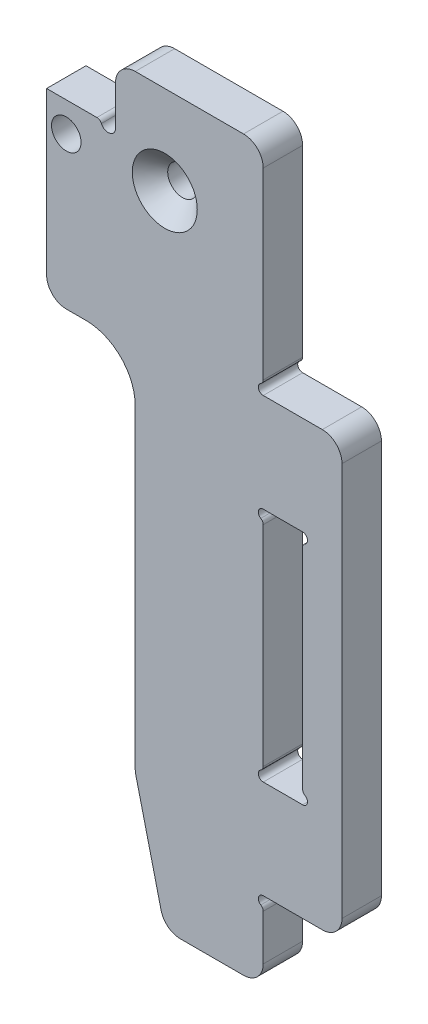
SolidWorks part; units mm, degrees
material "Thornel Mat VMA"
ref_plane "前视基准面" through (0, 0, 0) normal (0, 0, 1) x (1, 0, 0)
ref_plane "上视基准面" through (0, 0, 0) normal (0, 1, 0) x (1, 0, 0)
ref_plane "右视基准面" through (0, 0, 0) normal (1, 0, 0) x (0, 0, -1)
other "Configuration Table"
sketch "草图1" plane through (0, 0, 0) normal (0, 0, 1) x (1, 0, 0)
  line L0 (0, 0) -> (10, 0) construction
  line L1 (-5, -3) -> (10, -65)
  line L2 (-5, -3) -> (20, -3)
  line L3 (-5, -3) -> (-5, 3)
  line L4 (-5, 3) -> (20, 3)
  line L5 (20, -3) -> (20, 3)
  line L6 (-5, -3) -> (20, 3) construction
  line L7 (-5, 3) -> (20, -3) construction
  line L8 (5, 3) -> (20, 3)
  line L9 (5, 3) -> (5, 9)
  line L10 (5, 9) -> (20, 9)
  line L11 (20, 3) -> (20, 9)
  line L12 (10, -65) -> (20, -65)
  line L13 (20, -65) -> (20, -3)
  line L15 (24, -23) -> (20, -23)
  line L16 (24, -23) -> (24, -13)
  line L17 (24, -13) -> (20, -13)
  line L18 (20, -23) -> (20, -13)
  line L19 (24, -23) -> (20, -13) construction
  line L20 (24, -13) -> (20, -23) construction
  line L21 (24, -57) -> (20, -57)
  line L22 (24, -57) -> (24, -47)
  line L23 (24, -47) -> (20, -47)
  line L24 (20, -57) -> (20, -47)
  line L25 (24, -57) -> (20, -47) construction
  line L26 (24, -47) -> (20, -57) construction
  circle A0 centre (10, 0) radius 1.5
  circle A1 centre (0, 0) radius 1.5
  point P5 (7.5, 0)
  point P14 (22, -52)
  point P18 (22, -18)
  dimension "D2" = 3
  dimension "D4" = 5
  dimension "D5" = 10
  dimension "D1" = 10
  dimension "D3" = 68
  dimension "D6" = 6
  dimension "D7" = 15
  dimension "D8" = 6
  dimension "D9" = 10
  dimension "D10" = 8
  dimension "D11" = 16
  dimension "D12" = 4
  dimension "D13" = 10
extrude "凸台-拉伸1" add sketch "草图1" along normal blind 4 contours L4 L11 L10 L9 | L2 L5 L4 L3 A1 A0 | L12 L13 L2 L1 | L16 L17 L13 L15 | L22 L23 L13 L21
sketch "草图2" plane through (0, 0, 4) normal (0, 0, 1) x (1, 0, 0)
  line L0 (20, -13) -> (20, 9) construction
  line L1 (20, -47) -> (20, -23) construction
  line L2 (20, -65) -> (20, -57) construction
  line L3 (24, -57) -> (20, -57) construction
  line L4 (20, -12) -> (20, -58)
  line L5 (-5, 3) -> (5, 3) construction
  line L6 (5, 3) -> (3.5, 3)
  arc A0 (20, -13) -> (20, -12) centre (20, -12.5) cw
  arc A1 (20, -23) -> (20, -24) centre (20, -23.5) ccw
  arc A2 (20, -47) -> (20, -46) centre (20, -46.5) cw
  arc A3 (20, -57) -> (20, -58) centre (20, -57.5) ccw
  arc A4 (5, 3) -> (3.5, 3) centre (4.25, 3) cw
  line M5 (5, 3) -> (-5, 3)
  line M9 (20, -65) -> (20, -57)
  line M13 (20, -47) -> (20, -23)
  line M17 (20, -13) -> (20, 9)
  dimension "D1" = 0.5
  dimension "D2" = 0.75
extrude "切除-拉伸1" cut sketch "草图2" against normal up to surface (4 mm away) contours A0 M17 | L4 A1 | A2 M13 | A3 M9 | A4 M5 up to face at (15.0667, -25.9333, 0)
chamfer "倒角1" distance 1.8 angle 45 1 edges at (11.5, 0, 4)
sketch "草图3" plane through (0, 0, 4) normal (0, 0, 1) x (1, 0, 0)
  line L0 (24, -13) -> (20, -13) construction
  line L1 (24, -57) -> (28, -57)
  line L2 (24, -57) -> (24, -13)
  line L3 (24, -13) -> (28, -13)
  line L4 (28, -57) -> (28, -13)
  dimension "D1" = 4
extrude "凸台-拉伸2" add sketch "草图3" against normal up to surface (4 mm away) up to face at (11.5, 0, 0)
sketch "草图4" plane through (0, 0, 4) normal (0, 0, 1) x (1, 0, 0)
  line L0 (24, -23) -> (24, -47) construction
  line L1 (24, -47) -> (24, -23)
  arc A0 (24, -23) -> (24, -24) centre (24, -23.5) cw
  arc A1 (24, -47) -> (24, -46) centre (24, -46.5) ccw
  arc A2 (20, -23) -> (20, -24) centre (20, -23.5) ccw construction
  line M1 (24, -23) -> (24, -47)
extrude "切除-拉伸2" cut sketch "草图4" against normal up to surface (4 mm away) contours A0 M1 | A1 M1 up to face at (21.1667, -35, 0)
fillet "圆角1" radius 0.5 7 edges at (24, -24, 2) (24, -46, 2) (20, -24, 2) (20, -46, 2) (20, -58, 2) (3.5, 3, 2) (20, -12, 2)
sketch "草图6" plane through (0, 0, 0) normal (0, 0, -1) x (-1, 0, 0)
  line L0 (5, -3) -> (5, 24)
  line L1 (5, 24) -> (15, 24)
  line L2 (15, 24) -> (15, -3)
  line L3 (15, -3) -> (0, -65)
  line L4 (0, -65) -> (-10, -65)
  line L5 (-10, -65) -> (5, -3)
  line L6 (-5, 9) -> (-20, 9) construction
  line L7 (10, 24) -> (10, 19) construction
  circle A0 centre (10, 19) radius 2.5
  dimension "D3" = 5
  dimension "D1" = 10
  dimension "D2" = 15
  dimension "D4" = 5
extrude "凸台-拉伸3" [suppressed] add sketch "草图6" against normal up to surface (4 mm away)
sketch "草图7" [suppressed] plane through (0, 0, 0) normal (0, 0, -1) x (-1, 0, 0)
  line L0 (5, 4) -> (-3.1044, 4) construction
  line L1 (5, 25) -> (0.5, 25)
  line L2 (5, 25) -> (5, 4)
  line L3 (5, 4) -> (0.5, 4)
  line L4 (0.5, 25) -> (0.5, 4)
  dimension "D1" = 4.5
extrude "凸台-拉伸4" [suppressed] add sketch "草图7" against normal up to surface (4 mm away)
sketch "草图12" plane through (0, 0, 4) normal (0, 0, 1) x (1, 0, 0)
  line L0 (-5, -3) -> (10, -65) construction
  line L1 (-5, 3) -> (-2, 3)
  line L2 (-5, 3) -> (-5, -15.4)
  line L3 (-5, -15.4) -> (-2, -15.4)
  line L4 (-2, 3) -> (-2, -15.4)
  dimension "3" = 3
extrude "切除-拉伸6" cut sketch "草图12" against normal blind 10
sketch "草图13" plane through (0, 0, 4) normal (0, 0, 1) x (1, 0, 0)
  line L0 (7, -52.6) -> (-2, -15.4)
  line L1 (-2, -15.4) -> (10, -65) construction
  line L2 (-2, -15.4) -> (7, -15.4)
  line L3 (7, -15.4) -> (7, -52.6)
  line L4 (28, -57) -> (28, -13) construction
  dimension "D1" = 21
extrude "切除-拉伸7" cut sketch "草图13" against normal blind 10
fillet "圆角2" radius 5 1 edges at (7, -15.4, 2)
fillet "圆角3" radius 2 8 edges at (28, -13, 2) (28, -57, 2) (-2, -15.4, 2) (7, -52.6, 2) (5, 9, 2) (20, 9, 2) (20, -65, 2) (10, -65, 2)
